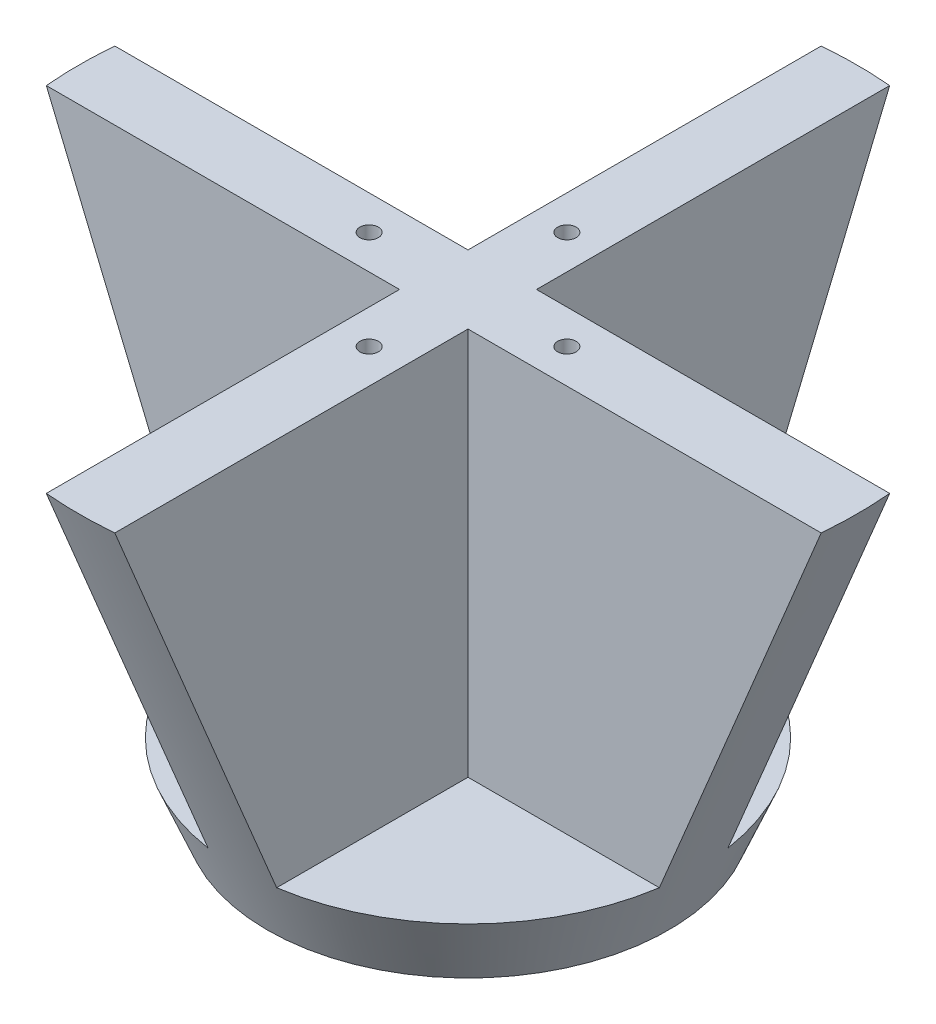
SolidWorks part; units mm, degrees
material "PE High Density"
ref_plane "Front Plane" through (0, 0, 0) normal (0, 0, 1) x (1, 0, 0)
ref_plane "Top Plane" through (0, 0, 0) normal (0, 1, 0) x (1, 0, 0)
ref_plane "Right Plane" through (0, 0, 0) normal (1, 0, 0) x (0, 0, -1)
sketch "Sketch1" plane through (0, 0, 0) normal (1, 0, 0) x (0, 0, -1)
  line L0 (0, 0) -> (0, -40473.1688) construction
  line L1 (0, 0) -> (-19.05, 0)
  line L2 (-19.05, 0) -> (-19.05, -5.08)
  line L3 (-19.05, -5.08) -> (-22.225, -5.08)
  line L4 (-22.225, -5.08) -> (-43.267, 45.72)
  line L5 (-43.267, 45.72) -> (0, 45.72)
  line L6 (0, 0) -> (0, 45.72)
  dimension "D1" = 19.05
  dimension "D2" = 3.175
  dimension "D3" = 22.5
  dimension "D4" = 50.8
  dimension "D5" = 5.08
revolve "Revolve1" add sketch "Sketch1" angle 360 about L0
sketch "Sketch2" plane through (0, 45.72, 0) normal (0, 1, 0) x (1, 0, 0)
  line L0 (0, 0) -> (50000, 0) construction
  line L1 (-3.81, -3.81) -> (-3.81, -43.099)
  line L2 (0, 0) -> (0, -50000) construction
  line L3 (-3.81, 43.099) -> (-3.81, 3.81)
  line L4 (3.81, -43.099) -> (3.81, -3.81)
  line L5 (-43.099, 3.81) -> (-3.81, 3.81)
  line L6 (-43.099, -3.81) -> (-3.81, -3.81)
  line L7 (3.81, 3.81) -> (43.099, 3.81)
  line L8 (3.81, 3.81) -> (3.81, 43.099)
  line L9 (3.81, -3.81) -> (43.099, -3.81)
  circle A0 centre (0, 0) radius 11 construction
  circle A1 centre (0, 11) radius 1.524 construction
  circle A2 centre (11, 0) radius 1.524 construction
  circle A3 centre (0, -11) radius 1.524 construction
  circle A4 centre (-11, 0) radius 1.524 construction
  circle A5 centre (0, 0) radius 43.267 construction
  arc A6 (-43.099, -3.81) -> (-3.81, -43.099) centre (0, 0) ccw
  arc A7 (43.099, 3.81) -> (3.81, 43.099) centre (0, 0) ccw
  arc A8 (3.81, -43.099) -> (43.099, -3.81) centre (0, 0) ccw
  arc A9 (-3.81, 43.099) -> (-43.099, 3.81) centre (0, 0) ccw
  dimension "D1" = 22
  dimension "D2" = 3.048
  dimension "D4" = 7.62
  dimension "D5" = 3.81
  dimension "D6" = 7.62
  dimension "D3" = 3.81
hole_wizard "M2.5x0.45 Tapped Hole1" positions "Sketch3" profile "Sketch4" tap size "M2.5x0.45" standard "ANSI Metric"
sketch "Sketch3" plane through (0, 45.72, 0) normal (0, 1, 0) x (1, 0, 0)
  point P0 (0, 11)
  point P3 (11, 0)
  point P6 (0, -11)
  point P9 (-11, 0)
sketch "Sketch4" plane through (0, 45.72, -11) normal (1, 0, 0) x (0, 0, 1)
  line L0 (0, 0) -> (0, 13.3159)
  line L1 (0, 13.3159) -> (1.025, 12.7)
  line L2 (1.025, 12.7) -> (1.025, 0)
  line L5 (1.025, 0) -> (0, 0)
  line L10 (0, 13.3159) -> (-1.025, 12.7) construction
  line L11 (0, -6.35) -> (0, 107.95) construction
  dimension "Tap Drill Dia." = 2.05
  dimension "Tap Drill Depth" = 12.7
  dimension "Drill Angle" = 118
cosmetic thread "Hole Thread1" parameters "D1"=5.08, "D2"=2.5
cosmetic thread "Hole Thread2" parameters "D1"=5.08, "D2"=2.5
cosmetic thread "Hole Thread3" parameters "D1"=5.08, "D2"=2.5
cosmetic thread "Hole Thread4" parameters "D1"=5.08, "D2"=2.5
extrude "cross_weight_reduction" cut sketch "Sketch2" against normal blind 43.18
sketch "Sketch5" plane through (0, -5.08, 0) normal (0, -1, 0) x (1, 0, 0)
  circle A0 centre (0, 0) radius 33.817
extrude "Cut-Extrude1" cut sketch "Sketch5" against normal blind 0.254
equation "\"D5@Sketch2\"=\"D4@Sketch2\"/2"
equation "\"D3@Sketch2\"=\"D4@Sketch2\"/2"
equation "\"D6@Sketch2\"=\"D4@Sketch2\""
